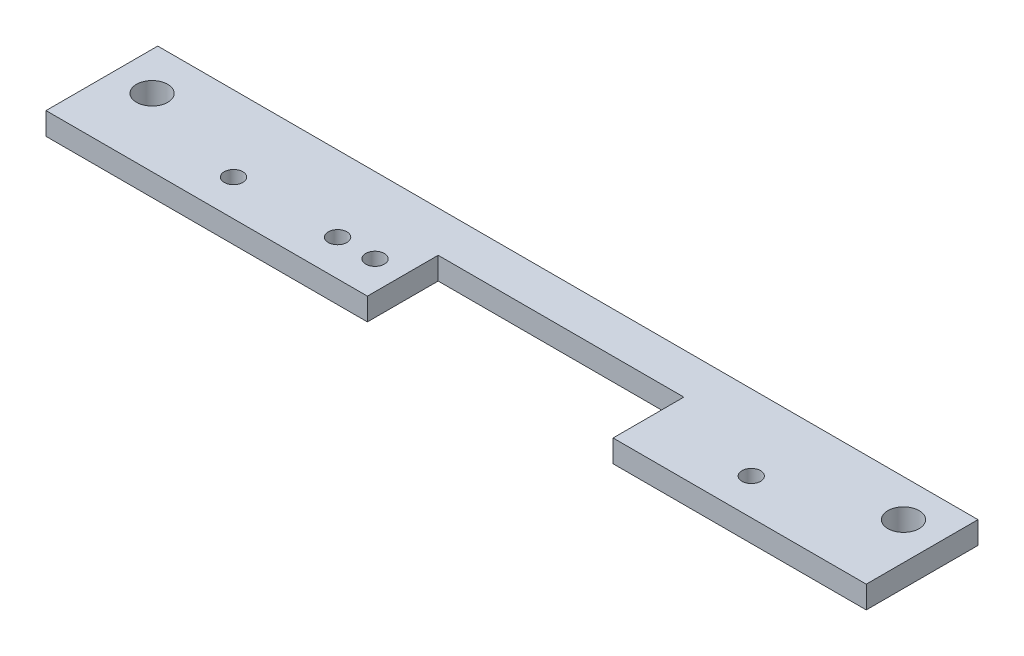
SolidWorks part; units mm, degrees
ref_plane "Alzado" through (0, 0, 0) normal (0, 0, 1) x (1, 0, 0)
ref_plane "Planta" through (0, 0, 0) normal (0, 1, 0) x (1, 0, 0)
ref_plane "Vista lateral" through (0, 0, 0) normal (1, 0, 0) x (0, 0, -1)
sketch "Croquis1" plane through (0, 0, 0) normal (0, 1, 0) x (1, 0, 0)
  line L1 (-55.055, -7.5) -> (55.055, -7.5)
  line L2 (-55.055, -7.5) -> (-55.055, 7.5)
  line L3 (-55.055, 7.5) -> (55.055, 7.5)
  line L4 (55.055, -7.5) -> (55.055, 7.5)
  line L5 (0, 7.5) -> (0, -7.5) construction
  line L6 (-55.055, 0) -> (55.055, 0) construction
  circle A0 centre (50.055, 2.5) radius 2.1
  circle A1 centre (-49.9412, 1.6273) radius 2.1
  circle A2 centre (-20.7659, -2.646) radius 1.25
  circle A3 centre (-34.7359, -2.646) radius 1.25
  circle A4 centre (-15.7359, -2.646) radius 1.25
  circle A5 centre (34.7641, -2.646) radius 1.25
  point P0 (0, 0)
  dimension "D1" = 110.11
  dimension "D2" = 15
extrude "Saliente-Extruir1" add sketch "Croquis1" along normal blind 3
ref_plane "Plano1" through (-55.055, 3, 7.5) normal (1, 0, 0) x (0, 0, -1)
sketch "Croquis4" plane through (0, 3, 0) normal (0, 1, 0) x (1, 0, 0)
  line L0 (-55.055, -7.5) -> (55.055, -7.5) construction
  line L1 (-11.9114, -7.5) -> (18.4433, -7.5)
  line L2 (-11.9114, -7.5) -> (-11.9114, 1.9996)
  line L3 (-11.9114, 1.9996) -> (18.4433, 1.9996)
  line L4 (18.4433, -7.5) -> (18.4433, 1.9996)
extrude "Cortar-Extruir2" cut sketch "Croquis4" against normal blind 3
sketch "Croquis5" plane through (0, 3, 0) normal (0, 1, 0) x (1, 0, 0)
  line L0 (18.4433, -7.5) -> (55.055, -7.5) construction
  line L1 (18.4433, 1.9996) -> (21.0684, 1.9996)
  line L2 (18.4433, 1.9996) -> (18.4433, -7.5)
  line L3 (18.4433, -7.5) -> (21.0684, -7.5)
  line L4 (21.0684, 1.9996) -> (21.0684, -7.5)
extrude "Cortar-Extruir3" cut sketch "Croquis5" against normal blind 3
